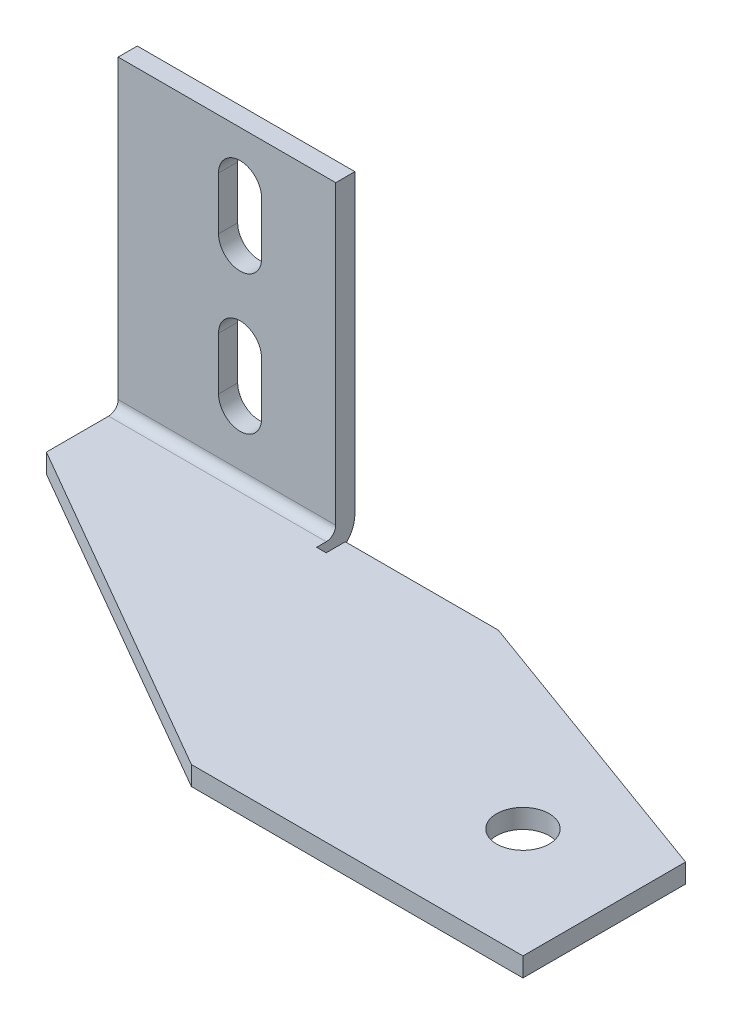
SolidWorks part; units mm, degrees
material "6061 合金"
ref_plane "前视基准面" through (0, 0, 0) normal (0, 0, 1) x (1, 0, 0)
ref_plane "上视基准面" through (0, 0, 0) normal (0, 1, 0) x (1, 0, 0)
ref_plane "右视基准面" through (0, 0, 0) normal (1, 0, 0) x (0, 0, -1)
other "Configuration Table"
sketch "草图1" plane through (0, 0, 0) normal (0, 1, 0) x (1, 0, 0)
  line L0 (0, 0) -> (39.7283, 0)
  line L1 (39.7283, 0) -> (70.5, -11.2)
  line L2 (70.5, -11.2) -> (70.5, -28.2)
  line L3 (70.5, -28.2) -> (35.8535, -28.2)
  line L4 (35.8535, -28.2) -> (0, -7.5)
  line L5 (0, -7.5) -> (0, 0)
  dimension "D1" = 7.5
  dimension "D2" = 70.5
  dimension "D3" = 28.2
  dimension "D4" = 160
  dimension "D5" = 120
  dimension "D6" = 17
extrude "凸台-拉伸1" add sketch "草图1" along normal blind 2
sketch "草图2" plane through (0, 2, 0) normal (0, 1, 0) x (1, 0, 0)
  line L0 (70.5, -28.2) -> (70.5, -11.2) construction
  line L1 (35.8535, -28.2) -> (70.5, -28.2) construction
  circle A0 centre (59, -16.7) radius 2.75
  dimension "D3" = 5.5
  dimension "D1" = 11.5
  dimension "D2" = 11.5
extrude "切除-拉伸1" cut sketch "草图2" against normal through all
sketch "草图3" plane through (0, 0, 0) normal (0, -1, 0) x (1, 0, 0)
  line L0 (0, 0) -> (22.7379, 0)
  line L1 (39.7283, 0) -> (0, 0) construction
  line L2 (22.7379, 0) -> (22.7379, -2)
  line L3 (22.7379, -2) -> (0, -2)
  line L4 (0, 0) -> (0, 7.5) construction
  line L5 (0, -2) -> (0, 0)
  dimension "D1" = 22.7379
  dimension "D2" = 2
extrude "凸台-拉伸2" add sketch "草图3" against normal blind 34
sketch "草图4" plane through (0, 0, 0) normal (0, 0, -1) x (-1, 0, 0)
  line L0 (-12.7379, 34) -> (-12.7379, 2) construction
  line L1 (0, 34) -> (-22.7379, 34) construction
  line L2 (-39.7283, 2) -> (-22.7379, 2) construction
  line L3 (-22.7379, 34) -> (-22.7379, 2) construction
  line L4 (-22.7379, 34) -> (0, 34) construction
  line L7 (0, 34) -> (0, 2) construction
  line L10 (0, 0) -> (-22.7379, 0) construction
  line L11 (-12.7379, 28.75) -> (-12.7379, 23.25) construction
  line L12 (-14.9879, 28.75) -> (-14.9879, 23.25)
  line L13 (-10.4879, 28.75) -> (-10.4879, 23.25)
  line L14 (-12.7379, 14.25) -> (-12.7379, 8.75) construction
  line L15 (-14.9879, 14.25) -> (-14.9879, 8.75)
  line L16 (-10.4879, 14.25) -> (-10.4879, 8.75)
  arc A4 (-14.9879, 28.75) -> (-10.4879, 28.75) centre (-12.7379, 28.75) cw
  arc A5 (-10.4879, 23.25) -> (-14.9879, 23.25) centre (-12.7379, 23.25) cw
  arc A6 (-14.9879, 14.25) -> (-10.4879, 14.25) centre (-12.7379, 14.25) cw
  arc A7 (-10.4879, 8.75) -> (-14.9879, 8.75) centre (-12.7379, 8.75) cw
  point P8 (-12.7379, 21)
  point P9 (-12.7379, 16.5)
  point P27 (-12.7379, 26)
  point P34 (-12.7379, 11.5)
  dimension "D2" = 5.5
  dimension "D7" = 5.25
  dimension "D4" = 2.25
  dimension "D5" = 2.25
  dimension "D1" = 10
  dimension "D3" = 5.5
  dimension "D6" = 4.5
  dimension "D8" = 12.7379
extrude "切除-拉伸2" cut sketch "草图4" along normal through all
sketch "草图7" plane through (0, 2, 0) normal (0, 1, 0) x (1, 0, 0)
  line L0 (22.7379, 0) -> (22.7379, -2)
  line L1 (22.7379, -2) -> (23.7379, -2)
  line L2 (23.7379, -2) -> (23.7379, 0)
  line L3 (39.7283, 0) -> (22.7379, 0) construction
  line L4 (23.7379, 0) -> (22.7379, 0)
  dimension "D1" = 2
  dimension "D2" = 1
extrude "切除-拉伸3" cut sketch "草图7" against normal blind 2
fillet "圆角1" radius 3 1 edges at (11.369, 0, -2)
fillet "圆角2" radius 1 1 edges at (11.369, 2, 0)
